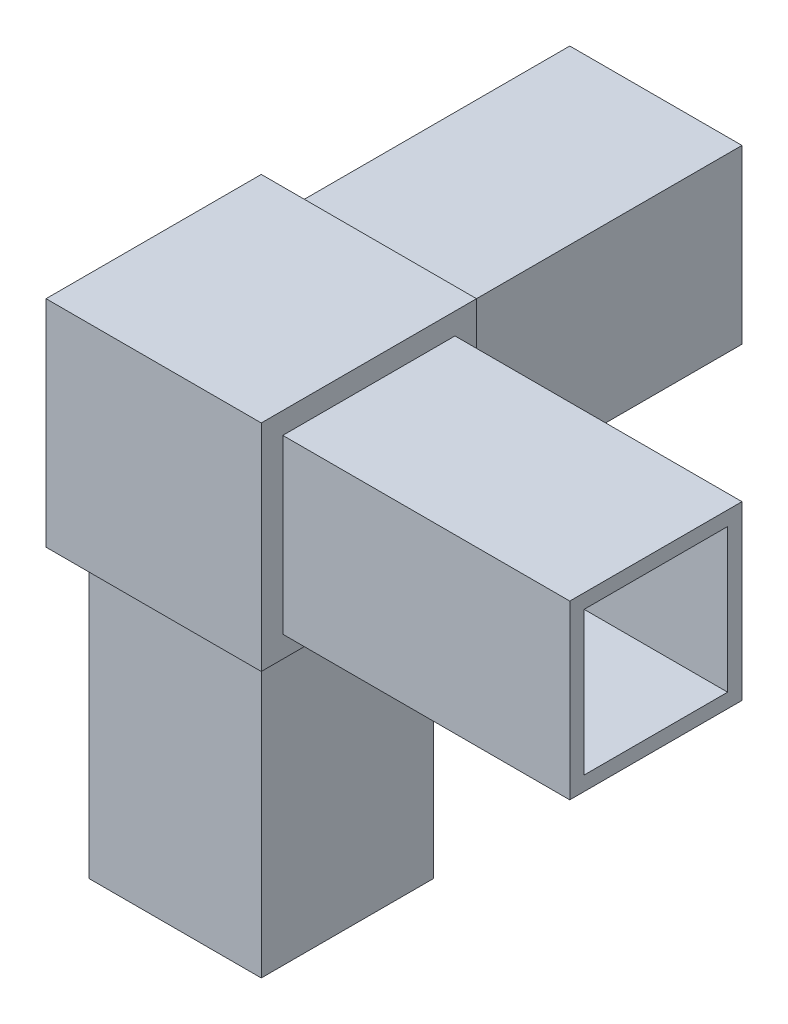
SolidWorks part; units mm, degrees
material "1060-H12"
ref_plane "Alzado" through (0, 0, 0) normal (0, 0, 1) x (1, 0, 0)
ref_plane "Planta" through (0, 0, 0) normal (0, 1, 0) x (1, 0, 0)
ref_plane "Vista lateral" through (0, 0, 0) normal (1, 0, 0) x (0, 0, -1)
sketch "Croquis1" plane through (0, 0, 0) normal (0, 1, 0) x (1, 0, 0)
  line L1 (15, -15) -> (-15, -15)
  line L2 (15, -15) -> (15, 15)
  line L3 (15, 15) -> (-15, 15)
  line L4 (-15, -15) -> (-15, 15)
  line L5 (15, -15) -> (-15, 15) construction
  line L6 (15, 15) -> (-15, -15) construction
  line L7 (15, -15) -> (55, -15)
  line L8 (15, -15) -> (15, 15)
  line L9 (15, 15) -> (55, 15)
  line L10 (55, -15) -> (55, 15)
  line L11 (-15, 15) -> (15, 15)
  line L12 (-15, 15) -> (-15, 55)
  line L13 (-15, 55) -> (15, 55)
  line L14 (15, 15) -> (15, 55)
  point P0 (0, 0)
  dimension "D2" = 30
  dimension "D3" = 40
  dimension "D4" = 40
extrude "Extruir1" add sketch "Croquis1" along normal blind 30 contours L3 L14 L13 L12 | L4 L1 L2 L3 | L7 L10 L9 L2
sketch "Croquis5" plane through (0, 0, 0) normal (0, -1, 0) x (1, 0, 0)
  line L1 (-15, 15) -> (15, 15)
  line L2 (-15, 15) -> (-15, -15)
  line L3 (-15, -15) -> (15, -15)
  line L4 (15, 15) -> (15, -15)
extrude "Extruir4" add sketch "Croquis5" along normal blind 40
sketch "Croquis2" plane through (55, 0, 0) normal (1, 0, 0) x (0, 0, -1)
  line L4 (-15, 0) -> (15, 0)
  line L5 (15, 0) -> (15, 30)
  line L6 (15, 30) -> (-15, 30)
  line L7 (-15, 30) -> (-15, 0)
  line L8 (-15, 0) -> (15, 0)
  line L9 (15, 0) -> (15, 30)
  line L10 (15, 30) -> (-15, 30)
  line L11 (-15, 30) -> (-15, 0)
  line L16 (-12, 3) -> (12, 3)
  line L17 (12, 3) -> (12, 27)
  line L18 (12, 27) -> (-12, 27)
  line L19 (-12, 27) -> (-12, 3)
  line L20 (-12, 3) -> (12, 3)
  line L21 (12, 3) -> (12, 27)
  line L22 (12, 27) -> (-12, 27)
  line L23 (-12, 27) -> (-12, 3)
  dimension "D1" = 0
  dimension "D2" = 3
extrude "Extruir2" cut sketch "Croquis2" against normal blind 40
sketch "Croquis3" plane through (0, 0, -55) normal (0, 0, -1) x (-1, 0, 0)
  line L0 (-12, 3) -> (12, 3)
  line L1 (12, 3) -> (12, 27)
  line L2 (12, 27) -> (-12, 27)
  line L3 (-12, 27) -> (-12, 3)
  line L4 (-15, 0) -> (15, 0)
  line L5 (15, 0) -> (15, 30)
  line L6 (15, 30) -> (-15, 30)
  line L7 (-15, 30) -> (-15, 0)
  line L8 (-15, 0) -> (15, 0)
  line L9 (15, 0) -> (15, 30)
  line L10 (15, 30) -> (-15, 30)
  line L11 (-15, 30) -> (-15, 0)
  dimension "D1" = 0
  dimension "D2" = 3
extrude "Extruir3" cut sketch "Croquis3" against normal blind 40
sketch "Croquis7" plane through (0, -40, 0) normal (0, -1, 0) x (1, 0, 0)
  line L0 (-12, 12) -> (-12, -12)
  line L1 (-12, -12) -> (12, -12)
  line L2 (12, -12) -> (12, 12)
  line L3 (12, 12) -> (-12, 12)
  line L4 (-15, 15) -> (-15, -15)
  line L5 (-15, -15) -> (15, -15)
  line L6 (15, -15) -> (15, 15)
  line L7 (15, 15) -> (-15, 15)
  line L8 (-15, 15) -> (-15, -15)
  line L9 (-15, -15) -> (15, -15)
  line L10 (15, -15) -> (15, 15)
  line L11 (15, 15) -> (-15, 15)
  dimension "D1" = 0
  dimension "D2" = 3
extrude "Extruir5" cut sketch "Croquis7" against normal blind 40
shell "Vaciado1" thickness 2
